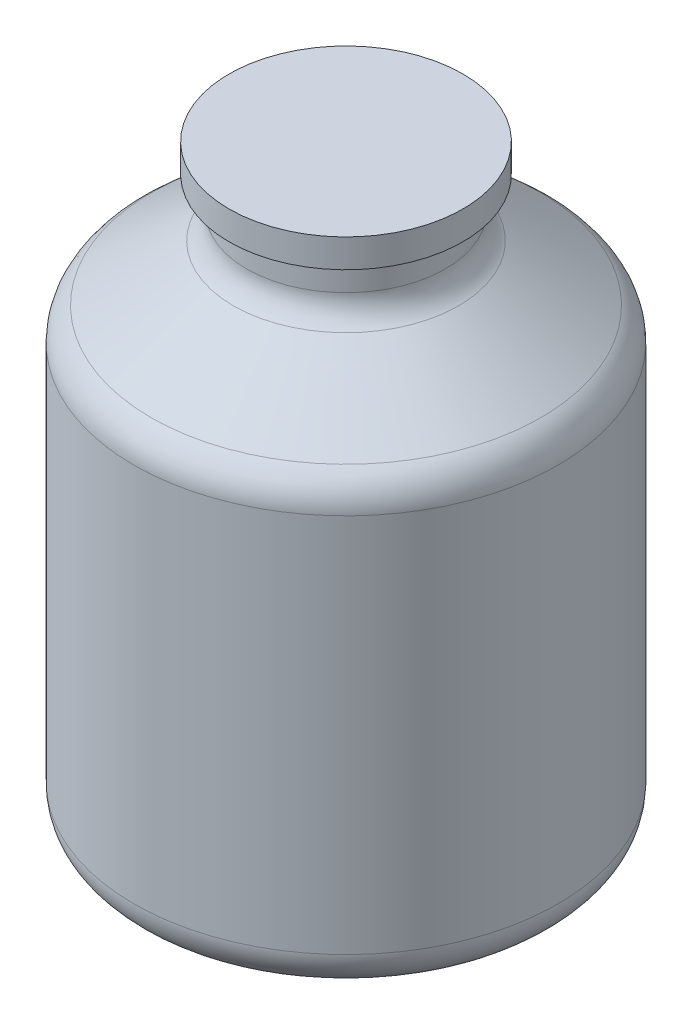
SolidWorks part; units mm, degrees
ref_plane "Front Plane" through (0, 0, 0) normal (0, 0, 1) x (1, 0, 0)
ref_plane "Top Plane" through (0, 0, 0) normal (0, 1, 0) x (1, 0, 0)
ref_plane "Right Plane" through (0, 0, 0) normal (1, 0, 0) x (0, 0, -1)
sketch "Sketch1" plane through (0, 0, 0) normal (0, 0, 1) x (1, 0, 0)
  line L0 (0, 0) -> (55.8506, 0)
  line L1 (68.5506, 12.7) -> (68.5506, 135.5371)
  line L2 (62.9889, 146.0411) -> (36.4262, 164.0924)
  line L3 (32.1096, 172.2449) -> (32.1096, 182.693)
  line L4 (32.1096, 182.693) -> (37.8125, 182.693)
  line L5 (37.8125, 182.693) -> (37.8125, 191.89)
  line L6 (37.8125, 191.89) -> (0, 191.89)
  line L7 (0, 191.89) -> (0, 0)
  arc A0 (55.8506, 0) -> (68.5506, 12.7) centre (55.8506, 12.7) ccw
  arc A1 (68.5506, 135.5371) -> (62.9889, 146.0411) centre (55.8506, 135.5371) ccw
  arc A2 (36.4262, 164.0924) -> (32.1096, 172.2449) centre (41.9665, 172.2449) cw
  point P11 (41.9665, 162.4248)
  point P16 (68.5506, 135.5371)
  dimension "D1" = 12.7
revolve "Revolve1" add sketch "Sketch1" angle 360 about L7
